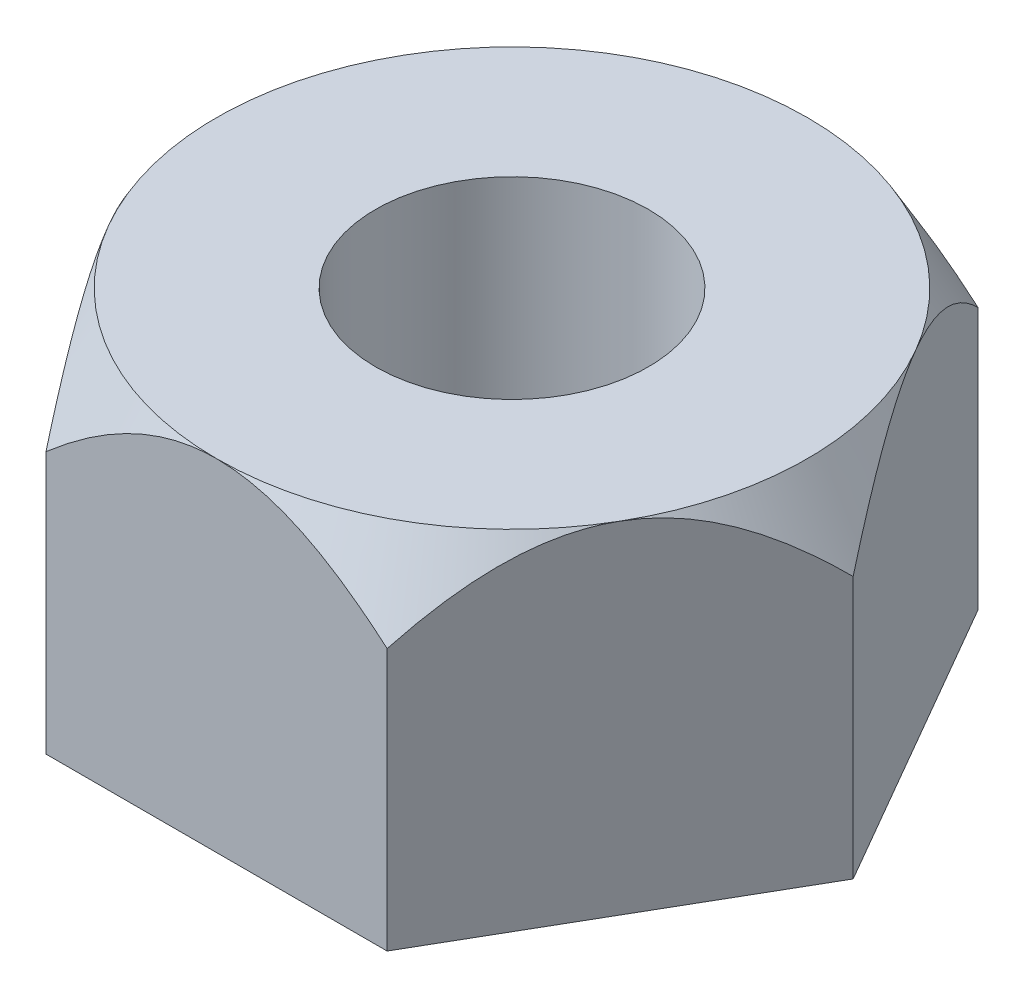
SolidWorks part; units mm, degrees
ref_plane "Front Plane" through (0, 0, 0) normal (0, 0, 1) x (1, 0, 0)
ref_plane "Top Plane" through (0, 0, 0) normal (0, 1, 0) x (1, 0, 0)
ref_plane "Right Plane" through (0, 0, 0) normal (1, 0, 0) x (0, 0, -1)
sketch "Sketch1" plane through (0, 0, 0) normal (0, 1, 0) x (1, 0, 0)
  line L1 (5, 0) -> (2.5, 4.3301)
  line L2 (2.5, 4.3301) -> (-2.5, 4.3301)
  line L3 (-2.5, 4.3301) -> (-5, 0)
  line L4 (-5, 0) -> (-2.5, -4.3301)
  line L5 (-2.5, -4.3301) -> (2.5, -4.3301)
  line L6 (2.5, -4.3301) -> (5, 0)
  circle A0 centre (0, 0) radius 4.3301 construction
  circle A1 centre (0, 0) radius 2
  dimension "D2" = 4
  dimension "D1" = 10
extrude "Boss-Extrude1" add sketch "Sketch1" along normal blind 5
sketch "Sketch2" plane through (0, 5, 0) normal (0, 1, 0) x (1, 0, 0)
  circle A0 centre (0, 0) radius 4.3301
extrude "Cut-Extrude1" cut sketch "Sketch2" against normal through all draft 30 flip side to cut
